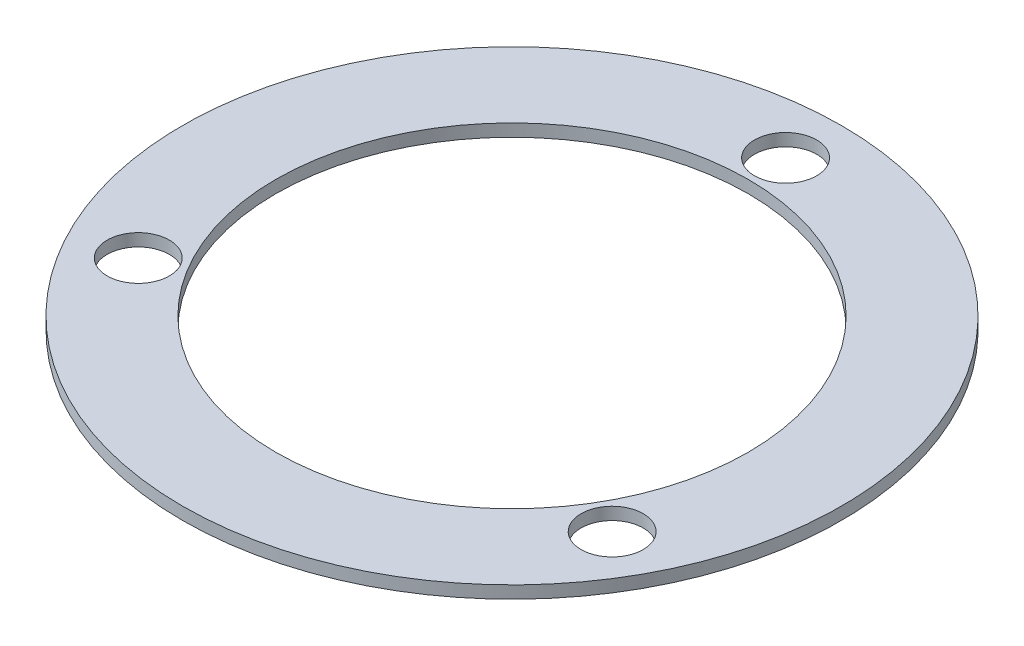
SolidWorks part; units mm, degrees
ref_plane "Front Plane" through (0, 0, 0) normal (0, 0, 1) x (1, 0, 0)
ref_plane "Top Plane" through (0, 0, 0) normal (0, 1, 0) x (1, 0, 0)
ref_plane "Right Plane" through (0, 0, 0) normal (1, 0, 0) x (0, 0, -1)
sketch "Sketch1" plane through (0, 0, 0) normal (0, 1, 0) x (1, 0, 0)
  circle A0 centre (0, 0) radius 9.5
  circle A1 centre (0, 0) radius 13.25
  circle A2 centre (0, 11) radius 1.25
  circle A3 centre (9.5263, -5.5) radius 1.25
  circle A4 centre (-9.5263, -5.5) radius 1.25
  point P12 (0, 0)
  dimension "D1" = 19
  dimension "D2" = 26.5
  dimension "D4" = 2.5
  dimension "D3" = 11
  dimension "D5" = 3
extrude "Boss-Extrude1" add sketch "Sketch1" along normal blind 0.5 contours A1
